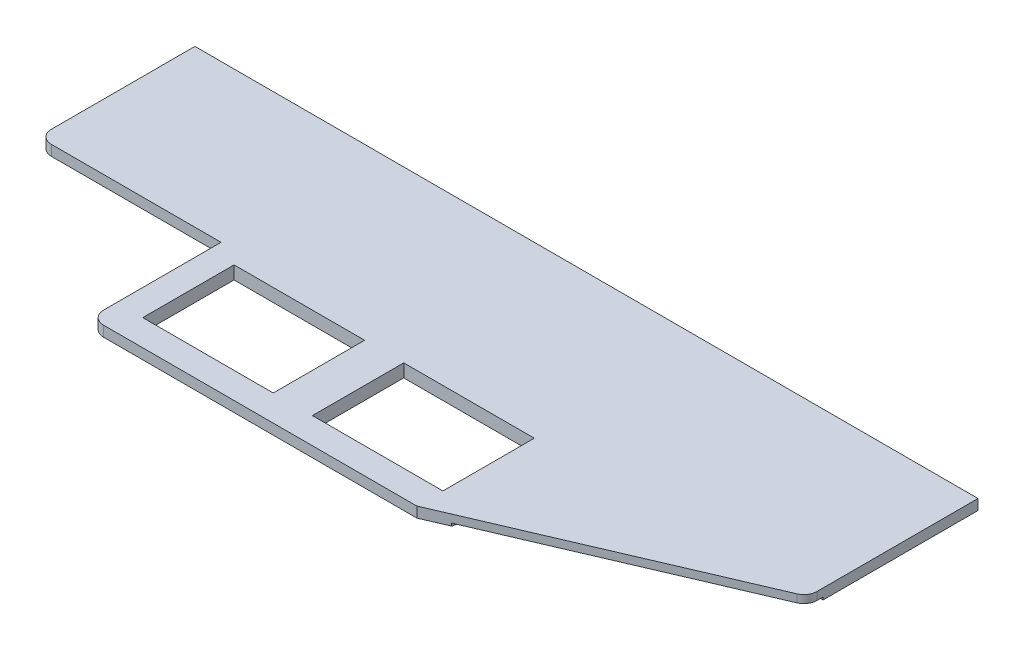
SolidWorks part; units mm, degrees
ref_plane "Front Plane" through (0, 0, 0) normal (0, 0, 1) x (1, 0, 0)
ref_plane "Top Plane" through (0, 0, 0) normal (0, 1, 0) x (1, 0, 0)
ref_plane "Right Plane" through (0, 0, 0) normal (1, 0, 0) x (0, 0, -1)
sketch "Sketch1" plane through (0, 0, 0) normal (0, 0, 1) x (1, 0, 0)
  line L0 (0, 0) -> (0, 254) construction
  line L1 (-381, 0) -> (0, 0)
  line L3 (-381, 6.35) -> (0, 6.35)
  line L4 (0, 0) -> (0, 6.35)
  line L5 (-381, 0) -> (-381, 6.35)
extrude "Boss-Extrude1" add sketch "Sketch1" along normal blind 139.7
sketch "Sketch2" plane through (0, 0, 0) normal (0, -1, 0) x (1, 0, 0)
  line L1 (-406.4, 139.7) -> (-406.4, 0) construction
  line L2 (-374.65, 76.2) -> (-292.1, 76.2)
  line L3 (-292.1, 76.2) -> (-292.1, 133.35)
  line L4 (-381, 139.7) -> (0, 139.7) construction
  line L5 (-285.75, 139.7) -> (-133.35, 139.7)
  line L6 (-133.35, 139.7) -> (-3.8486, 84.1994)
  line L7 (0, 139.7) -> (0, 0) construction
  line L8 (0, 78.3628) -> (0, 0)
  line L9 (0, 0) -> (-381, 0)
  line L10 (-381, 69.85) -> (-381, 0)
  line L11 (-381, 139.7) -> (-381, 0) construction
  arc A0 (-3.8486, 84.1994) -> (0, 78.3628) centre (-6.35, 78.3628) cw
  arc A1 (-292.1, 133.35) -> (-285.75, 139.7) centre (-285.75, 133.35) cw
  arc A3 (-381, 69.85) -> (-374.65, 76.2) centre (-374.65, 69.85) cw
  point P17 (0, 82.55)
  point P20 (-292.1, 139.7)
  point P21 (-381, 76.2)
  point P23 (-406.4, 76.2)
  dimension "D5" = 6.35
  dimension "D1" = 6.35
  dimension "D2" = 114.3
  dimension "D3" = 158.75
  dimension "D4" = 82.55
extrude "Cut-Extrude1" cut sketch "Sketch2" against normal through all
sketch "Sketch3" plane through (0, 6.35, 0) normal (0, 1, 0) x (1, 0, 0)
  line L0 (-133.35, -139.7) -> (-285.75, -139.7) construction
  line L1 (-279.4, -127) -> (-215.9, -127)
  line L2 (-279.4, -127) -> (-279.4, -82.55)
  line L3 (-279.4, -82.55) -> (-215.9, -82.55)
  line L4 (-215.9, -127) -> (-215.9, -82.55)
  line L5 (-196.85, -127) -> (-133.35, -127)
  line L6 (-196.85, -127) -> (-196.85, -82.55)
  line L7 (-196.85, -82.55) -> (-133.35, -82.55)
  line L8 (-133.35, -127) -> (-133.35, -82.55)
  line L9 (-292.1, -76.2) -> (-292.1, -133.35) construction
  dimension "D1" = 44.45
  dimension "D2" = 12.7
  dimension "D3" = 12.7
  dimension "D4" = 63.5
  dimension "D5" = 19.05
  dimension "D6" = 44.45
  dimension "D7" = 12.7
  dimension "D8" = 63.5
extrude "Cut-Extrude2" cut sketch "Sketch3" against normal through all contours L5 L8 L7 L6 | L1 L4 L3 L2
sketch "Sketch4" plane through (0, 0, 0) normal (0, -1, 0) x (1, 0, 0)
  line L0 (-285.75, 139.7) -> (-133.35, 139.7) construction
  line L1 (-279.4, 133.35) -> (-215.9, 133.35)
  line L2 (-285.75, 127) -> (-285.75, 25.4)
  line L3 (-279.4, 19.05) -> (-215.9, 19.05)
  line L4 (-209.55, 127) -> (-209.55, 25.4)
  line L5 (-127, 133.35) -> (-196.85, 133.35)
  line L7 (-131.8807, 19.05) -> (-196.85, 19.05)
  line L8 (-203.2, 127) -> (-203.2, 25.4)
  line L9 (-292.1, 76.2) -> (-292.1, 133.35) construction
  line L11 (-381, 0) -> (0, 0) construction
  line L12 (-215.9, 127) -> (-215.9, 82.55) construction
  line L13 (-127, 133.35) -> (-112.1376, 74.8789)
  line L14 (-112.1376, 74.8789) -> (-125.7444, 23.7664)
  arc A0 (-196.85, 133.35) -> (-203.2, 127) centre (-196.85, 127) ccw
  arc A1 (-215.9, 133.35) -> (-209.55, 127) centre (-215.9, 127) cw
  arc A2 (-279.4, 133.35) -> (-285.75, 127) centre (-279.4, 127) ccw
  arc A3 (-285.75, 25.4) -> (-279.4, 19.05) centre (-279.4, 25.4) ccw
  arc A4 (-215.9, 19.05) -> (-209.55, 25.4) centre (-215.9, 25.4) ccw
  arc A5 (-196.85, 19.05) -> (-203.2, 25.4) centre (-196.85, 25.4) cw
  arc A6 (-131.8807, 19.05) -> (-125.7444, 23.7664) centre (-131.8807, 25.4) ccw
  dimension "D3" = 6.35
  dimension "D1" = 6.35
  dimension "D2" = 6.35
  dimension "D4" = 6.35
  dimension "D5" = 19.05
  dimension "D6" = 6.35
  dimension "D7" = 6.35
  dimension "D8" = 19.05
extrude "Cut-Extrude3" cut sketch "Sketch4" against normal blind 1.27
sketch "Sketch5" plane through (0, 0, 0) normal (0, -1, 0) x (1, 0, 0)
  line L0 (-250.8616, 56.914) -> (-269.3149, 71.6766)
  line L1 (-248.4216, 50.9666) -> (-248.4331, 50.9773) construction
  line L3 (-267.7282, 76.2) -> (-229.317, 76.2)
  line L4 (-257.258, 53.8991) -> (-275.2733, 68.3113)
  line L5 (-184.3234, 76.2) -> (-133.6398, 76.2)
  line L6 (-196.85, 82.55) -> (-133.35, 82.55) construction
  line L9 (-142.8427, 29.9409) -> (-159.4602, 42.9343)
  line L10 (-227.2884, 29.9234) -> (-246.082, 44.9583)
  line L12 (-131.9836, 71.533) -> (-158.9921, 53.9033)
  line L15 (-124.9851, 68.5182) -> (-151.5288, 51.1918)
  line L21 (-220.0267, 32.246) -> (-239.6856, 47.9731)
  line L24 (-275.269, 33.4756) -> (-257.2515, 47.954)
  line L26 (-131.8807, 25.4) -> (-118.6989, 74.9159)
  line L28 (-131.8807, 25.4) -> (-118.6989, 74.9159)
  line L30 (-118.6989, 74.9159) -> (-131.9379, 127)
  line L37 (-269.5564, 29.9199) -> (-250.8486, 44.9531)
  line L38 (-215.9, 34.2294) -> (-215.9, 67.7374)
  line L40 (-248.5328, 50.9091) -> (-248.3486, 51.0351) construction
  line L41 (-246.095, 56.9191) -> (-227.7259, 71.6801)
  line L42 (-248.5328, 50.9091) -> (-248.5037, 50.8894) construction
  line L43 (-228.8751, 25.4) -> (-267.9653, 25.4)
  line L44 (-248.3486, 51.0351) -> (-248.5037, 50.8894) construction
  line L45 (-279.4, 66.3279) -> (-279.4, 35.4556)
  line L46 (-239.6921, 53.9182) -> (-220.031, 69.7173)
  line L47 (-133.6398, 76.2) -> (-133.372, 76.2)
  line L51 (-134.0223, 31.1049) -> (-151.793, 45)
  line L55 (-163.4215, 54.0923) -> (-185.888, 71.6591)
  line L57 (-164.1074, 50.5642) -> (-164.3654, 50.8) construction
  line L58 (-131.9379, 127) -> (-196.85, 127)
  line L59 (-171.3529, 45.8348) -> (-192.9216, 31.7558)
  line L60 (-164.3654, 50.8) -> (-164.0586, 50.5961) construction
  line L61 (-196.85, 127) -> (-196.85, 25.4)
  line L62 (-164.0586, 50.5961) -> (-164.1074, 50.5642)
  line L63 (-171.0886, 52.0266) -> (-192.7454, 68.9603)
  line L65 (-163.8896, 43.1233) -> (-183.8917, 30.067)
  line L66 (-196.85, 127) -> (-196.85, 25.4)
  line L68 (-196.85, 25.4) -> (-131.8807, 25.4)
  line L70 (-196.85, 25.4) -> (-131.8807, 25.4)
  arc A0 (-257.258, 53.8991) -> (-257.2515, 47.954) centre (-259.6381, 50.924) cw
  arc A1 (-250.8486, 44.9531) -> (-246.082, 44.9583) centre (-248.462, 41.9831) cw
  arc A2 (-239.6856, 47.9731) -> (-239.6921, 53.9182) centre (-237.3055, 50.9483) cw
  arc A3 (-250.8616, 56.914) -> (-246.095, 56.9191) centre (-248.4815, 59.8891) ccw
  arc A4 (-267.7282, 76.2) -> (-269.3149, 71.6766) centre (-267.7282, 73.66) ccw
  arc A5 (-275.2733, 68.3113) -> (-279.4, 66.3279) centre (-276.86, 66.3279) ccw
  arc A6 (-279.4, 35.4556) -> (-275.269, 33.4756) centre (-276.86, 35.4556) ccw
  arc A7 (-267.9653, 25.4) -> (-269.5564, 29.9199) centre (-267.9653, 27.94) cw
  arc A8 (-227.2884, 29.9234) -> (-228.8751, 25.4) centre (-228.8751, 27.94) cw
  arc A9 (-220.0267, 32.246) -> (-215.9, 34.2294) centre (-218.44, 34.2294) ccw
  arc A10 (-215.9, 67.7374) -> (-220.031, 69.7173) centre (-218.44, 67.7374) ccw
  arc A11 (-227.7259, 71.6801) -> (-229.317, 76.2) centre (-229.317, 73.66) ccw
  arc A12 (-183.8917, 30.067) -> (-182.5033, 25.4) centre (-182.5033, 27.94) ccw
  arc A13 (-142.8427, 29.9409) -> (-144.4073, 25.4) centre (-144.4073, 27.94) cw
  arc A14 (-124.9851, 68.5182) -> (-121.1422, 65.7378) centre (-123.5967, 66.3912) cw
  arc A15 (-133.372, 76.2) -> (-131.9836, 71.533) centre (-133.372, 73.66) cw
  arc A16 (-134.0223, 31.1049) -> (-130.0033, 32.4524) centre (-132.4578, 33.1058) ccw
  arc A17 (-192.9216, 31.7558) -> (-196.85, 33.8828) centre (-194.31, 33.8828) cw
  arc A18 (-196.85, 66.9593) -> (-192.7454, 68.9603) centre (-194.31, 66.9593) cw
  arc A19 (-185.888, 71.6591) -> (-184.3234, 76.2) centre (-184.3234, 73.66) cw
  arc A20 (-171.3529, 45.8348) -> (-171.0886, 52.0266) centre (-173.4355, 49.0252) ccw
  arc A21 (-163.8896, 43.1233) -> (-159.4602, 42.9343) centre (-161.807, 39.9329) cw
  arc A22 (-151.793, 45) -> (-151.5288, 51.1918) centre (-149.4462, 48.0014) cw
  arc A23 (-158.9921, 53.9033) -> (-163.4215, 54.0923) centre (-161.0746, 57.0937) cw
  point P13 (-247.9043, 50.4821)
  point P14 (-248.3486, 51.0351)
  point P39 (-243.3962, 50.9416)
  point P55 (-157.9377, 50.8)
  point P56 (-164.3654, 50.8)
  point P88 (-166.8929, 48.746)
  dimension "D5" = 3.81
  dimension "D1" = 2.54
  dimension "D4" = 2.54
  dimension "D6" = 2.54
  dimension "D7" = 2.54
  dimension "D8" = 3.81
  dimension "D3" = 6.35
  dimension "D2" = 6.35
extrude "Cut-Extrude4" cut sketch "Sketch5" against normal blind 1.27 contours A23 L12 A15 L47 L5 A19 L55 | A22 L51 A16 L28 A14 L15 | A21 L65 A12 L70 A13 L9 | L59 A20 L63 A18 L66 A17 | L38 A10 L46 A2 L21 A9 | A8 L10 A1 L37 A7 L43 | L41 A11 L3 A4 L0 A3 | L45 A6 L24 A0 L4 A5
sketch "Sketch6" plane through (0, 1.27, 0) normal (0, -1, 0) x (1, 0, 0)
  line L0 (-288.798, 6.985) -> (-288.798, 13.335) construction
  line L1 (-291.846, 6.985) -> (-291.846, 13.335)
  line L2 (-285.75, 6.985) -> (-285.75, 13.335)
  line L3 (-270.002, 6.985) -> (-270.002, 13.335) construction
  line L6 (-273.05, 6.985) -> (-273.05, 13.335)
  line L9 (-266.954, 6.985) -> (-266.954, 13.335)
  line L12 (-251.206, 6.985) -> (-251.206, 13.335) construction
  line L15 (-381, 0) -> (0, 0) construction
  line L17 (-254.254, 6.985) -> (-254.254, 13.335)
  line L18 (-248.158, 6.985) -> (-248.158, 13.335)
  line L19 (-162.56, 6.985) -> (-162.56, 13.335) construction
  line L20 (-165.608, 6.985) -> (-165.608, 13.335)
  line L21 (-159.512, 6.985) -> (-159.512, 13.335)
  line L22 (-143.764, 6.985) -> (-143.764, 13.335) construction
  line L23 (-146.812, 6.985) -> (-146.812, 13.335)
  line L24 (-140.716, 6.985) -> (-140.716, 13.335)
  line L25 (-124.968, 6.985) -> (-124.968, 13.335) construction
  line L26 (-128.016, 6.985) -> (-128.016, 13.335)
  line L27 (-121.92, 6.985) -> (-121.92, 13.335)
  line L28 (-381, 69.85) -> (-381, 0) construction
  arc A0 (-291.846, 6.985) -> (-285.75, 6.985) centre (-288.798, 6.985) ccw
  arc A1 (-285.75, 13.335) -> (-291.846, 13.335) centre (-288.798, 13.335) ccw
  arc A5 (-286.5205, 4.8853) -> (-286.5215, 4.9583) centre (-289.4119, 4.8853) ccw
  arc A7 (-286.5205, 4.8853) -> (-286.5215, 4.9583) centre (-289.4119, 4.8853) ccw
  arc A9 (-286.5205, 4.8853) -> (-286.5215, 4.9583) centre (-289.4119, 4.8853) ccw
  arc A10 (-273.05, 6.985) -> (-266.954, 6.985) centre (-270.002, 6.985) ccw
  arc A11 (-266.954, 13.335) -> (-273.05, 13.335) centre (-270.002, 13.335) ccw
  arc A12 (-254.254, 6.985) -> (-248.158, 6.985) centre (-251.206, 6.985) ccw
  arc A13 (-248.158, 13.335) -> (-254.254, 13.335) centre (-251.206, 13.335) ccw
  arc A14 (-165.608, 6.985) -> (-159.512, 6.985) centre (-162.56, 6.985) ccw
  arc A15 (-159.512, 13.335) -> (-165.608, 13.335) centre (-162.56, 13.335) ccw
  arc A16 (-146.812, 6.985) -> (-140.716, 6.985) centre (-143.764, 6.985) ccw
  arc A17 (-140.716, 13.335) -> (-146.812, 13.335) centre (-143.764, 13.335) ccw
  arc A18 (-128.016, 6.985) -> (-121.92, 6.985) centre (-124.968, 6.985) ccw
  arc A19 (-121.92, 13.335) -> (-128.016, 13.335) centre (-124.968, 13.335) ccw
  point P2 (-288.798, 10.16)
  point P9 (-289.4119, -1.7103)
  point P11 (-270.002, 10.16)
  point P16 (-289.4119, 0)
  point P18 (-251.206, 10.16)
  point P23 (-289.4119, 0)
  point P28 (-162.56, 10.16)
  point P30 (-289.4119, 0)
  point P41 (-143.764, 10.16)
  point P48 (-124.968, 10.16)
  point P57 (-248.158, 10.16)
  dimension "D1" = 3.048
  dimension "D2" = 6.35
  dimension "D3" = 10.16
  dimension "D4" = 95.25
  dimension "D5" = 12.7
  dimension "D6" = 12.7
  dimension "D7" = 82.55
  dimension "D8" = 12.7
  dimension "D9" = 12.7
extrude "Cut-Extrude5" cut sketch "Sketch6" against normal blind 1.27 contours L18 A13 L17 A12 | L21 A15 L20 A14 | L24 A17 L23 A16 | L27 A19 L26 A18 | L9 A11 L6 A10 | L2 A1 L1 A0
sketch "Sketch7" plane through (0, 1.27, 0) normal (0, -1, 0) x (1, 0, 0)
  ellipse E0 centre (-102.3292, 61.2539) end of major axis (-102.3292, 71.8921) minor radius 7.2651
extrude "Boss-Extrude2" add sketch "Sketch7" along normal blind 1.27
sketch "Sketch8" plane through (0, 0, 0) normal (0, -1, 0) x (1, 0, 0)
  spline S0 degree 3 poles (-102.5457, 53.1558) (-102.1128, 53.1558) (-101.9017, 53.1847) (-101.4887, 53.2926) (-101.286, 53.3725) (-100.9061, 53.5658) (-100.7263, 53.6798) (-100.3826, 53.9355) (-100.2199, 54.0767) (-99.7641, 54.523) (-99.4978, 54.8539) (-99.0202, 55.5645) (-98.8146, 55.9368) (-98.4565, 56.7025) (-98.3038, 57.0969) (-98.0439, 57.9056) (-97.9369, 58.3207) (-97.6852, 59.5649) (-97.6045, 60.4029) (-97.604, 61.6715) (-97.6245, 62.0987) (-97.7076, 62.9434) (-97.7697, 63.3607) (-98.0198, 64.5967) (-98.2685, 65.4004) (-98.8106, 66.5641) (-99.0169, 66.9375) (-99.4909, 67.6447) (-99.7614, 67.9817) (-100.2165, 68.4281) (-100.3767, 68.5675) (-100.7186, 68.8228) (-100.9015, 68.9393) (-101.2816, 69.1335) (-101.4804, 69.2125) (-101.8977, 69.3226) (-102.1082, 69.3513) (-102.5329, 69.3528) (-102.7497, 69.3244) (-103.1637, 69.2174) (-103.3649, 69.1387) (-103.748, 68.9447) (-103.9279, 68.8308) (-104.2697, 68.5773) (-104.4325, 68.4367) (-104.8923, 67.9876) (-105.1581, 67.6571) (-105.6325, 66.9527) (-105.8414, 66.5759) (-106.381, 65.423) (-106.6338, 64.6169) (-106.8884, 63.364) (-106.9508, 62.9429) (-107.0335, 62.1027) (-107.0541, 61.6823) (-107.0545, 60.8405) (-107.0345, 60.4193) (-106.9523, 59.576) (-106.8897, 59.1521) (-106.6374, 57.9049) (-106.3864, 57.0988) (-105.8458, 55.9402) (-105.6383, 55.5651) (-105.2832, 55.0361) (-105.1572, 54.8648) (-104.8873, 54.5343) (-104.7428, 54.3746) (-104.4383, 54.0765) (-104.2778, 53.9373) (-103.9365, 53.6828) (-103.7539, 53.5667) (-103.3731, 53.3727) (-103.175, 53.2943) (-102.7592, 53.185) (-102.5457, 53.1558) (-102.1128, 53.1558) (-101.9017, 53.1847) knots -0.015625 -0.015625 0 0 0.015625 0.015625 0.03125 0.03125 0.046875 0.046875 0.0625 0.0625 0.09375 0.09375 0.125 0.125 0.15625 0.15625 0.1875 0.1875 0.25 0.25 0.28125 0.28125 0.3125 0.3125 0.375 0.375 0.40625 0.40625 0.4375 0.4375 0.453125 0.453125 0.46875 0.46875 0.484375 0.484375 0.5 0.5 0.515625 0.515625 0.53125 0.53125 0.546875 0.546875 0.5625 0.5625 0.59375 0.59375 0.625 0.625 0.6875 0.6875 0.71875 0.71875 0.75 0.75 0.78125 0.78125 0.8125 0.8125 0.875 0.875 0.90625 0.90625 0.921875 0.921875 0.9375 0.9375 0.953125 0.953125 0.96875 0.96875 0.984375 0.984375 1 1 1.015625 1.015625 1.03125 only from (-102.3292, 53.1558) to (-102.3292, 53.1558)
  spline S1 degree 3 poles (-102.5457, 53.1558) (-102.1128, 53.1558) (-101.9017, 53.1847) (-101.4887, 53.2926) (-101.286, 53.3725) (-100.9061, 53.5658) (-100.7263, 53.6798) (-100.3826, 53.9355) (-100.2199, 54.0767) (-99.7641, 54.523) (-99.4978, 54.8539) (-99.0202, 55.5645) (-98.8146, 55.9368) (-98.4565, 56.7025) (-98.3038, 57.0969) (-98.0439, 57.9056) (-97.9369, 58.3207) (-97.6852, 59.5649) (-97.6045, 60.4029) (-97.604, 61.6715) (-97.6245, 62.0987) (-97.7076, 62.9434) (-97.7697, 63.3607) (-98.0198, 64.5967) (-98.2685, 65.4004) (-98.8106, 66.5641) (-99.0169, 66.9375) (-99.4909, 67.6447) (-99.7614, 67.9817) (-100.2165, 68.4281) (-100.3767, 68.5675) (-100.7186, 68.8228) (-100.9015, 68.9393) (-101.2816, 69.1335) (-101.4804, 69.2125) (-101.8977, 69.3226) (-102.1082, 69.3513) (-102.5329, 69.3528) (-102.7497, 69.3244) (-103.1637, 69.2174) (-103.3649, 69.1387) (-103.748, 68.9447) (-103.9279, 68.8308) (-104.2697, 68.5773) (-104.4325, 68.4367) (-104.8923, 67.9876) (-105.1581, 67.6571) (-105.6325, 66.9527) (-105.8414, 66.5759) (-106.381, 65.423) (-106.6338, 64.6169) (-106.8884, 63.364) (-106.9508, 62.9429) (-107.0335, 62.1027) (-107.0541, 61.6823) (-107.0545, 60.8405) (-107.0345, 60.4193) (-106.9523, 59.576) (-106.8897, 59.1521) (-106.6374, 57.9049) (-106.3864, 57.0988) (-105.8458, 55.9402) (-105.6383, 55.5651) (-105.2832, 55.0361) (-105.1572, 54.8648) (-104.8873, 54.5343) (-104.7428, 54.3746) (-104.4383, 54.0765) (-104.2778, 53.9373) (-103.9365, 53.6828) (-103.7539, 53.5667) (-103.3731, 53.3727) (-103.175, 53.2943) (-102.7592, 53.185) (-102.5457, 53.1558) (-102.1128, 53.1558) (-101.9017, 53.1847) knots -0.015625 -0.015625 0 0 0.015625 0.015625 0.03125 0.03125 0.046875 0.046875 0.0625 0.0625 0.09375 0.09375 0.125 0.125 0.15625 0.15625 0.1875 0.1875 0.25 0.25 0.28125 0.28125 0.3125 0.3125 0.375 0.375 0.40625 0.40625 0.4375 0.4375 0.453125 0.453125 0.46875 0.46875 0.484375 0.484375 0.5 0.5 0.515625 0.515625 0.53125 0.53125 0.546875 0.546875 0.5625 0.5625 0.59375 0.59375 0.625 0.625 0.6875 0.6875 0.71875 0.71875 0.75 0.75 0.78125 0.78125 0.8125 0.8125 0.875 0.875 0.90625 0.90625 0.921875 0.921875 0.9375 0.9375 0.953125 0.953125 0.96875 0.96875 0.984375 0.984375 1 1 1.015625 1.015625 1.03125 only from (-102.3292, 53.1558) to (-102.3292, 53.1558)
  dimension "D1" = 2.54
extrude "Cut-Extrude6" cut sketch "Sketch8" against normal blind 2.54
sketch "Sketch9" plane through (0, 1.27, 0) normal (0, -1, 0) x (1, 0, 0)
  circle A0 centre (-20.3877, 60.8315) radius 7.62
  dimension "D1" = 15.24
extrude "Boss-Extrude3" add sketch "Sketch9" along normal blind 1.27
sketch "Sketch10" plane through (0, 0, 0) normal (0, -1, 0) x (1, 0, 0)
  circle A2 centre (-20.3877, 60.8315) radius 5.08
  circle A3 centre (-20.3877, 60.8315) radius 5.08
  dimension "D1" = 2.54
extrude "Cut-Extrude7" cut sketch "Sketch10" against normal blind 2.54
sketch "Sketch13" plane through (0, 1.27, 0) normal (0, -1, 0) x (1, 0, 0)
  line L0 (-119.1478, 125.4549) -> (-106.4217, 75.3886)
  line L1 (-106.4217, 75.3886) -> (0, 75.3886)
  line L2 (0, 0) -> (0, 78.3628) construction
  line L3 (-119.1478, 125.4549) -> (-121.475, 134.6107)
  line L4 (-3.8486, 84.1994) -> (-133.35, 139.7) construction
  line L5 (0, 75.3886) -> (0, 78.3628)
  line L6 (-3.8486, 84.1994) -> (-121.475, 134.6107)
  arc A0 (0, 78.3628) -> (-3.8486, 84.1994) centre (-6.35, 78.3628) ccw construction
  arc A1 (0, 78.3628) -> (-3.8486, 84.1994) centre (-6.35, 78.3628) ccw
extrude "Cut-Extrude10" cut sketch "Sketch13" against normal blind 1.27 contours L5 A1 L6 L3 L0 L1
sketch "Sketch14" plane through (0, 1.27, 0) normal (0, -1, 0) x (1, 0, 0)
  line L1 (-355.6, 72.8674) -> (-344.17, 72.8674)
  line L2 (-355.6, 72.8674) -> (-355.6, 66.5174)
  line L3 (-355.6, 66.5174) -> (-344.17, 66.5174)
  line L4 (-344.17, 72.8674) -> (-344.17, 66.5174)
  line L6 (-381, 69.85) -> (-381, 0) construction
  circle A0 centre (-370.84, 62.8553) radius 5.08
  dimension "D1" = 10.16
  dimension "D5" = 10.16
  dimension "D2" = 25.4
  dimension "D3" = 6.35
  dimension "D4" = 11.43
extrude "Boss-Extrude4" add sketch "Sketch14" along normal blind 1.27
ref_plane "Plane2" through (0, 3.175, 0) normal (0, -1, 0) x (-1, 0, 0)
